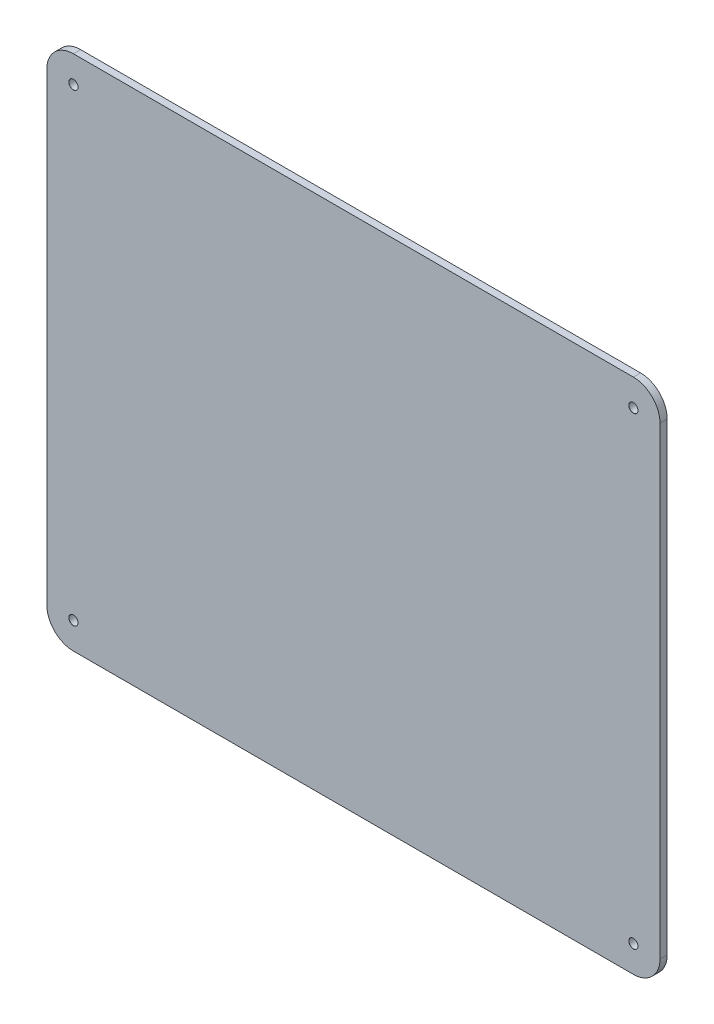
SolidWorks part; units mm, degrees
ref_plane "Front Plane" through (0, 0, 0) normal (0, 0, 1) x (1, 0, 0)
ref_plane "Top Plane" through (0, 0, 0) normal (0, 1, 0) x (1, 0, 0)
ref_plane "Right Plane" through (0, 0, 0) normal (1, 0, 0) x (0, 0, -1)
sketch "Sketch1" plane through (0, 0, 0) normal (0, 0, 1) x (1, 0, 0)
  line L1 (0, -250) -> (-210, -250)
  line L2 (10, -240) -> (10, -65.9884)
  line L3 (0, -55.9884) -> (-210, -55.9884)
  line L4 (-220, -240) -> (-220, -65.9884)
  arc A0 (-210, -250) -> (-220, -240) centre (-210, -240) cw
  arc A1 (0, -250) -> (10, -240) centre (0, -240) ccw
  arc A2 (10, -65.9884) -> (0, -55.9884) centre (0, -65.9884) ccw
  arc A3 (-210, -55.9884) -> (-220, -65.9884) centre (-210, -65.9884) ccw
  dimension "D1" = 10
extrude "Boss-Extrude1" add sketch "Sketch1" along normal blind 2.7
hole_wizard "M3 Clearance Hole1" positions "3DSketch1" profile "Sketch2" hole size "M3" standard "AS" end condition through all
sketch3d "3DSketch1"
  line L0 (-210, -250, 2.7) -> (0, -250, 2.7) construction
  line L1 (10, -240, 2.7) -> (10, -65.9884, 2.7) construction
  line L2 (0, -55.9884, 2.7) -> (-210, -55.9884, 2.7) construction
  line L3 (-220, -65.9884, 2.7) -> (-220, -240, 2.7) construction
  point P0 (0, -240, 2.7)
  point P7 (-210, -240, 2.7)
  point P9 (-210, -65.9884, 2.7)
  point P11 (0, -65.9884, 2.7)
  dimension "D1" = 10
  dimension "D2" = 10
  dimension "D3" = 10
  dimension "D4" = 10
  dimension "D5" = 10
  dimension "D6" = 10
  dimension "D7" = 10
  dimension "D8" = 10
sketch "Sketch2" plane through (0, -240, 2.7) normal (1, 0, 0) x (0, -1, 0)
  line L0 (0, 0) -> (0, 2.7)
  line L1 (0, 2.7) -> (1.7, 2.7)
  line L2 (1.7, 2.7) -> (1.7, 0.025)
  line L3 (1.7, 0.025) -> (1.725, 0)
  line L5 (1.725, 0) -> (0, 0)
  line L6 (-1.7, 0.025) -> (-1.725, 0) construction
  line L11 (0, -6.35) -> (0, 107.95) construction
  dimension "Thru Hole Dia." = 3.4
  dimension "Thru Hole Depth" = 2.7
  dimension "Near C'Sink Dia." = 3.45
  dimension "Near C'Sink Angle" = 90
